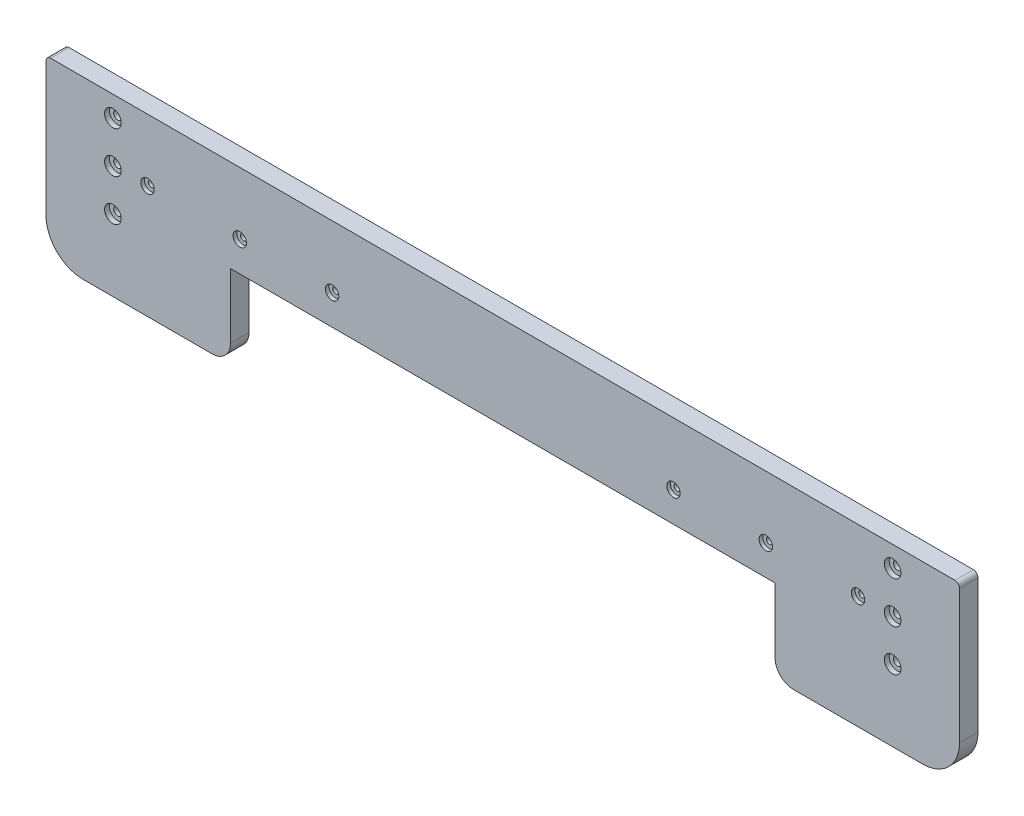
SolidWorks part; units mm, degrees
material "6061 Alloy"
ref_plane "Front Plane" through (0, 0, 0) normal (0, 0, 1) x (1, 0, 0)
ref_plane "Top Plane" through (0, 0, 0) normal (0, 1, 0) x (1, 0, 0)
ref_plane "Right Plane" through (0, 0, 0) normal (1, 0, 0) x (0, 0, -1)
sketch "Sketch1" plane through (0, 0, 0) normal (0, 0, 1) x (1, 0, 0)
  line L0 (-495, 33.1177) -> (-495, 178.1177)
  line L1 (-490, 183.1177) -> (490, 183.1177)
  line L2 (495, 178.1177) -> (495, 33.1177)
  line L3 (455, -6.8823) -> (315, -6.8823)
  line L4 (295, 13.1177) -> (295, 83.1177)
  line L5 (295, 83.1177) -> (-295, 83.1177)
  line L6 (-295, 83.1177) -> (-295, 13.1177)
  line L7 (-315, -6.8823) -> (-455, -6.8823)
  line L8 (0, 183.1177) -> (0, -96.8627) construction
  line L9 (-495, 160.6177) -> (495, 160.6177) construction
  arc A0 (490, 183.1177) -> (495, 178.1177) centre (490, 178.1177) cw
  arc A1 (-495, 178.1177) -> (-490, 183.1177) centre (-490, 178.1177) cw
  arc A2 (315, -6.8823) -> (295, 13.1177) centre (315, 13.1177) cw
  arc A3 (-295, 13.1177) -> (-315, -6.8823) centre (-315, 13.1177) cw
  arc A4 (495, 33.1177) -> (455, -6.8823) centre (455, 33.1177) cw
  arc A5 (-495, 33.1177) -> (-455, -6.8823) centre (-455, 33.1177) ccw
  point P15 (495, 183.1177)
  point P18 (-495, 183.1177)
  point P21 (295, -6.8823)
  point P24 (-295, -6.8823)
  point P27 (495, -6.8823)
  point P30 (-495, -6.8823)
  dimension "D1" = 495
  dimension "D9" = 5
  dimension "D10" = 20
  dimension "D11" = 40
  dimension "D2" = 22.5
  dimension "D3" = 190
  dimension "D4" = 190
  dimension "D5" = 200
  dimension "D6" = 200
  dimension "D7" = 990
  dimension "D8" = 100
extrude "Boss-Extrude1" add sketch "Sketch1" along normal blind 20
hole_wizard "1 Rc Tapped Hole1" positions "Sketch2" profile "Sketch4" size "1" standard "DIN"
sketch "Sketch2" plane through (0, 0, 20) normal (0, 0, 1) x (1, 0, 0)
  point P0 (395.4554, 41.9732)
sketch "Sketch4" plane through (395.4554, 41.9732, 20) normal (1, 0, 0) x (0, -1, 0)
  line L0 (0, 0) -> (0, 20)
  line L1 (0, 20) -> (13.5, 20)
  line L3 (13.5, 20) -> (13.5, 19)
  line L4 (13.5, 19) -> (16.0322, 19)
  line L5 (16.0322, 19) -> (16.6245, 0.025)
  line L6 (16.6245, 0.025) -> (16.6495, 0)
  line L7 (16.6495, 0) -> (0, 0)
  line L8 (0, -6.35) -> (0, 107.95) construction
  line L9 (-16.6245, 0.025) -> (-16.6495, 0) construction
  line L11 (-13.5, 19) -> (-16.0322, 19) construction
  line L12 (-16.0322, 19) -> (-16.6245, 0.025) construction
  dimension "Thru Tap Drill Dia." = 27
  dimension "Thru Tap Drill Depth" = 20
  dimension "Thread Dia." = 33.249
  dimension "Thread Angle" = 3.576
  dimension "Thread Depth" = 19
  dimension "Near C'Sink Dia." = 33.299
  dimension "Near C'Sink Angle" = 90
hole_wizard "CBORE for M8 Hex Head Bolt1" positions "Sketch5" profile "Sketch6" counterbore size "M8" standard "DIN" end condition up to next
sketch "Sketch5" plane through (0, 0, 20) normal (0, 0, 1) x (1, 0, 0)
  line L0 (490, 183.1177) -> (-490, 183.1177) construction
  point P0 (-422.5, 160.6177)
  point P2 (-422.5, 115.6177)
  point P10 (-1342.1281, 1089.9069)
  point P19 (-422.5, 70.6177)
  dimension "D1" = 422.5
  dimension "D3" = 22.5
  dimension "D4" = 45
  dimension "D5" = 45
sketch "Sketch6" plane through (-422.5, 160.6177, 20) normal (1, 0, 0) x (0, -1, 0)
  line L0 (0, 0) -> (0, 20)
  line L1 (0, 20) -> (4.5, 20)
  line L3 (4.5, 20) -> (4.5, 5.3)
  line L4 (9.0055, 5.3) -> (4.5, 5.3)
  line L5 (9.0055, 5.3) -> (9.0055, 0.025)
  line L6 (9.0055, 0.025) -> (9.0305, 0)
  line L7 (9.0305, 0) -> (0, 0)
  line L8 (-9.0055, 0.025) -> (-9.0305, 0) construction
  line L11 (0, -6.35) -> (0, 107.95) construction
  dimension "Thru Hole Dia." = 9
  dimension "Thru Hole Depth" = 20
  dimension "C'Bore Dia." = 18.011
  dimension "C'Bore Depth" = 5.3
  dimension "Near C'Sink Dia." = 18.061
  dimension "Near C'Sink Angle" = 90
mirror "Mirror1" about plane through (0, 0, 0) normal (1, 0, 0) of "CBORE for M8 Hex Head Bolt1"
hole_wizard "CBORE for M6 Hex Head Bolt1" positions "Sketch7" profile "Sketch8" counterbore size "M6" standard "DIN" end condition up to next
sketch "Sketch7" plane through (0, 0, 20) normal (0, 0, 1) x (1, 0, 0)
  line L0 (0, -11) -> (0, 11) construction
  line L1 (490, 183.1177) -> (-490, 183.1177) construction
  point P0 (-385, 115.6177)
  point P2 (-285, 115.6177)
  point P4 (-185, 115.6177)
  dimension "D1" = 385
  dimension "D2" = 100
  dimension "D3" = 100
  dimension "D4" = 67.5
sketch "Sketch8" plane through (-385, 115.6177, 20) normal (1, 0, 0) x (0, -1, 0)
  line L0 (0, 0) -> (0, 20.001)
  line L1 (0, 20.001) -> (3.3, 20.001)
  line L3 (3.3, 20.001) -> (3.3, 4)
  line L4 (7.2735, 4) -> (3.3, 4)
  line L5 (7.2735, 4) -> (7.2735, 0.025)
  line L6 (7.2735, 0.025) -> (7.2985, 0)
  line L7 (7.2985, 0) -> (0, 0)
  line L8 (-7.2735, 0.025) -> (-7.2985, 0) construction
  line L11 (0, -6.35) -> (0, 107.95) construction
  dimension "Thru Hole Dia." = 6.6
  dimension "Thru Hole Depth" = 20.001
  dimension "C'Bore Dia." = 14.547
  dimension "C'Bore Depth" = 4
  dimension "Near C'Sink Dia." = 14.597
  dimension "Near C'Sink Angle" = 90
mirror "Mirror2" about plane through (0, 0, 0) normal (1, 0, 0) of "CBORE for M6 Hex Head Bolt1"
